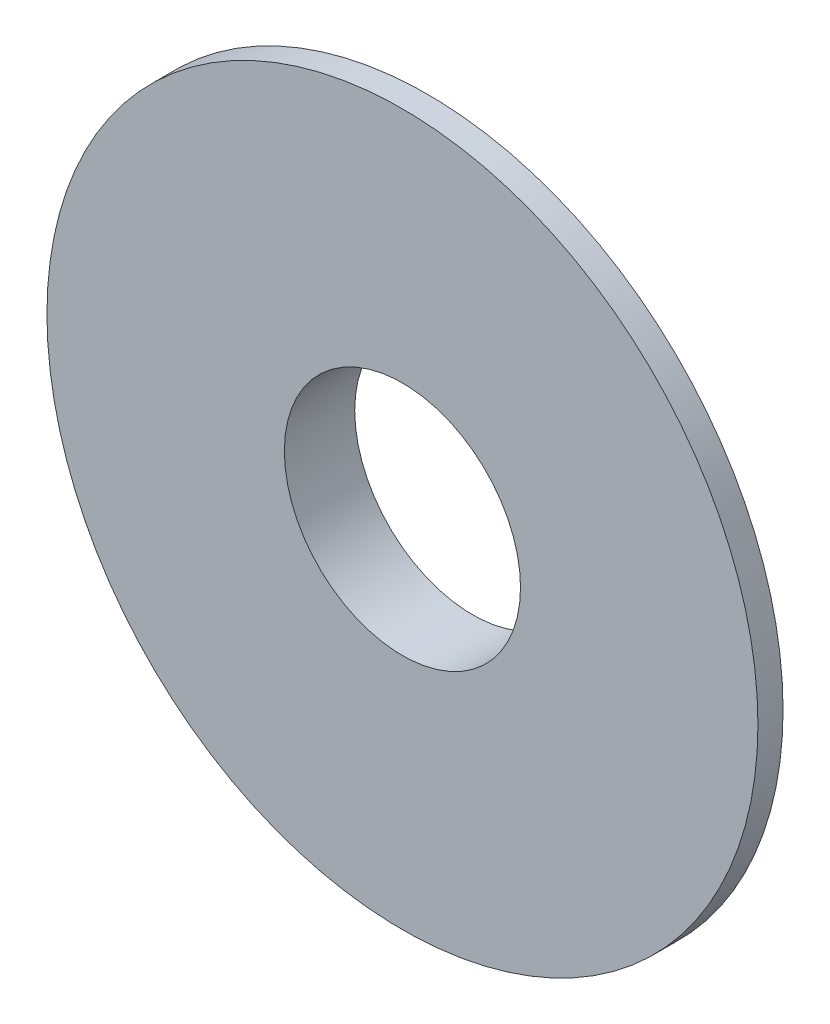
SolidWorks part; units mm, degrees
ref_plane "Спереди" through (0, 0, 0) normal (0, 0, 1) x (1, 0, 0)
ref_plane "Сверху" through (0, 0, 0) normal (0, 1, 0) x (1, 0, 0)
ref_plane "Справа" through (0, 0, 0) normal (1, 0, 0) x (0, 0, -1)
sketch "Эскиз1" plane through (0, 0, 0) normal (0, 0, 1) x (1, 0, 0)
  circle A0 centre (0, 0) radius 70.7538
  circle A1 centre (0, 0) radius 23.5
extrude "Cover_web" add sketch "Эскиз1" along normal blind 5 from offset 35
sketch "Эскиз2" plane through (0, 0, 0) normal (0, 0, 1) x (1, 0, 0)
  circle A0 centre (0, 0) radius 27.5
  circle A1 centre (0, 0) radius 23.5
extrude "Bearing_boss" add sketch "Эскиз2" along normal blind 14 from offset 26
